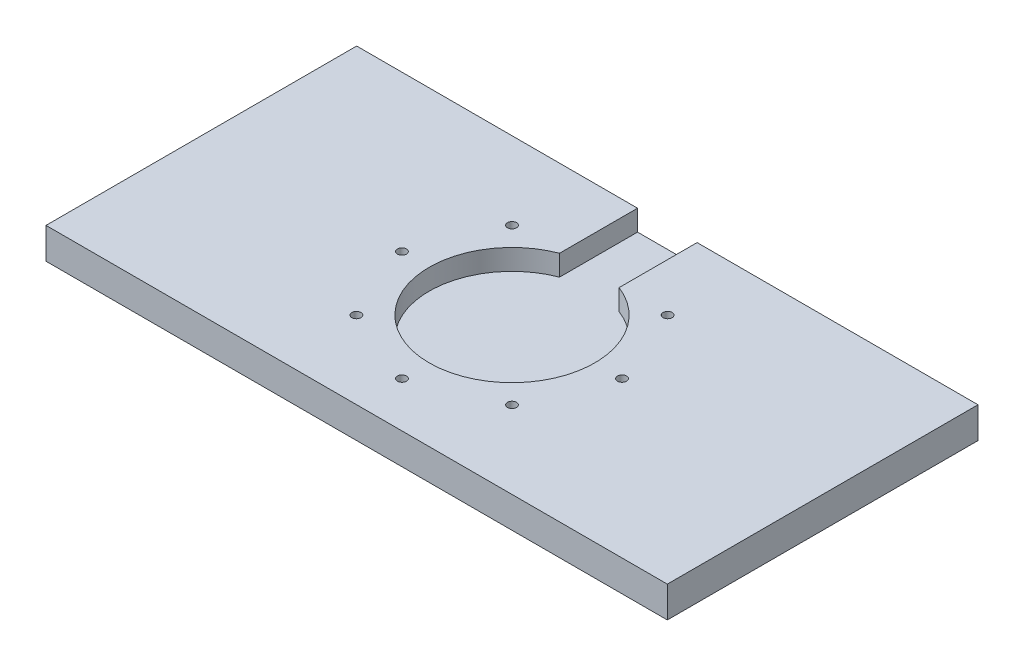
SolidWorks part; units mm, degrees
ref_plane "Front Plane" through (0, 0, 0) normal (0, 0, 1) x (1, 0, 0)
ref_plane "Top Plane" through (0, 0, 0) normal (0, 1, 0) x (1, 0, 0)
ref_plane "Right Plane" through (0, 0, 0) normal (1, 0, 0) x (0, 0, -1)
sketch "Sketch1" plane through (0, 0, 0) normal (0, 1, 0) x (1, 0, 0)
  line L1 (-120, 60) -> (120, 60)
  line L2 (-120, 60) -> (-120, -60)
  line L3 (-120, -60) -> (120, -60)
  line L4 (120, 60) -> (120, -60)
  dimension "D1" = 60
  dimension "D2" = 120
  dimension "D3" = 240
  dimension "D4" = 120
extrude "Boss-Extrude1" add sketch "Sketch1" against normal blind 12 contours L1 L4 L3 L2
sketch "Sketch2" plane through (0, 0, 0) normal (0, 1, 0) x (1, 0, 0)
  circle A0 centre (0, 0) radius 32
extrude "Cut-Extrude1" cut sketch "Sketch2" against normal blind 8 contours A0
sketch "Sketch3" plane through (0, 0, 0) normal (0, 1, 0) x (1, 0, 0)
  line L0 (-120, 60) -> (120, 60) construction
  line L1 (-11.5, 29.5336) -> (11.5, 29.5336)
  line L2 (-11.5, 29.5336) -> (-11.5, 60)
  line L3 (-11.5, 60) -> (11.5, 60)
  line L4 (11.5, 29.5336) -> (11.5, 60)
  dimension "D1" = 11.5
extrude "Cut-Extrude2" cut sketch "Sketch3" against normal blind 8 contours L1 L4 L3 L2
sketch "Sketch4" plane through (0, 0, 0) normal (0, 1, 0) x (1, 0, 0)
  circle A0 centre (-42.5, 0) radius 1.75
  arc A1 (-11.5, 29.8622) -> (11.5, 29.8622) centre (0, 0) ccw construction
  circle A2 centre (-30.052, 30.052) radius 1.75
  circle A4 centre (30.052, 30.052) radius 1.75
  circle A5 centre (42.5, 0) radius 1.75
  circle A6 centre (30.052, -30.052) radius 1.75
  circle A7 centre (0, -42.5) radius 1.75
  circle A8 centre (-30.052, -30.052) radius 1.75
  circle A9 centre (0, 42.5) radius 1.75 [skipped]
  point P12 (0, 0)
  point P15 (0, 0)
  point P18 (0, 0)
  point P21 (0, 0)
  point P26 (0, 0)
  dimension "D1" = 42.5
  dimension "D2" = 8
extrude "Cut-Extrude4" cut sketch "Sketch4" against normal blind 20
sketch "Sketch5" plane through (0, -12, 0) normal (0, 1, 0) x (1, 0, 0)
  circle A0 centre (-42.5, 0) radius 3
  circle A1 centre (-30.052, 30.052) radius 3
  circle A3 centre (30.052, 30.052) radius 3
  circle A4 centre (42.5, 0) radius 3
  circle A5 centre (30.052, -30.052) radius 3
  circle A6 centre (0, -42.5) radius 3
  circle A7 centre (-30.052, -30.052) radius 3
  circle A8 centre (0, 42.5) radius 3 [skipped]
  point P20 (0, 0)
  dimension "D1" = 8
extrude "Cut-Extrude7" cut sketch "Sketch5" along normal blind 5
